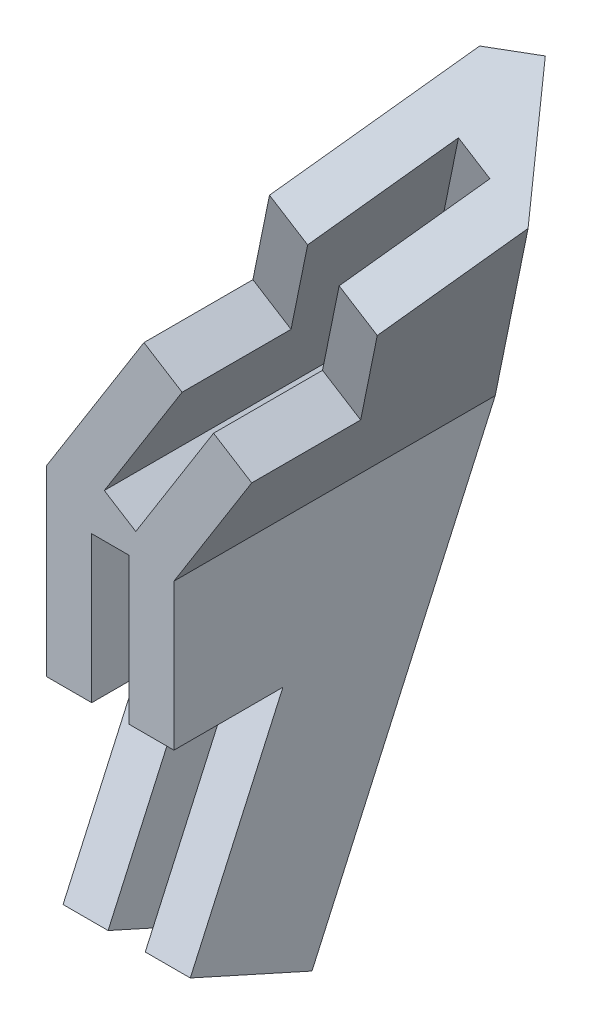
SolidWorks part; units mm, degrees
ref_plane "Front Plane" through (0, 0, 0) normal (0, 0, 1) x (1, 0, 0)
ref_plane "Top Plane" through (0, 0, 0) normal (0, 1, 0) x (1, 0, 0)
ref_plane "Right Plane" through (0, 0, 0) normal (1, 0, 0) x (0, 0, -1)
sketch "Sketch7" plane through (0, 0, 0) normal (0, 0, 1) x (1, 0, 0)
  line L0 (-1.7, -2) -> (-1.7, -15)
  line L1 (-1.7, -15) -> (-5.7, -15)
  line L2 (-5.7, -15) -> (-5.7, -2)
  line L3 (-5.7, -2) -> (-9, -2)
  line L4 (-9, -2) -> (-9, -15)
  line L5 (-9, -15) -> (-13, -15)
  line L7 (-13, -15) -> (-13, 1.2509)
  line L9 (-1.7, -2) -> (-13, 1.2509)
extrude "Boss-Extrude3" add sketch "Sketch7" along normal blind 30
sketch "Sketch11" plane through (-13, 0, 0) normal (-1, 0, 0) x (0, 0, 1)
  line L0 (0, 1.2509) -> (7.3231, -15)
  line L2 (30, -15) -> (0, -15) construction
  line L3 (7.3231, -15) -> (0, -15)
  line L4 (0, -15) -> (0, 1.2509)
extrude "Cut-Extrude1" cut sketch "Sketch11" against normal through all
sketch "Sketch12" plane through (0, -15, 0) normal (0, -1, 0) x (-1, 0, 0)
  line L0 (13, -7.3231) -> (9, -7.3231)
  line L1 (9, -7.3231) -> (9, -20.3231)
  line L2 (9, -30) -> (9, -7.3231) construction
  line L3 (13, -7.3231) -> (13, -20.3231)
  line L4 (13, -30) -> (13, -7.3231) construction
  line L5 (13, -20.3231) -> (9, -20.3231)
  line L6 (1.7, -7.3231) -> (1.7, -20.3231)
  line L7 (1.7, -30) -> (1.7, -7.3231) construction
  line L8 (1.7, -20.3231) -> (5.7, -20.3231)
  line L9 (5.7, -30) -> (5.7, -7.3231) construction
  line L10 (5.7, -20.3231) -> (5.7, -7.3231)
  line L11 (5.7, -7.3231) -> (1.7, -7.3231)
extrude "Boss-Extrude4" add sketch "Sketch12" along direction (0, 0.9117, -0.4108) on the side of the normal blind 30
sketch "Sketch18" plane through (0, -42.3512, 0) normal (0, -1, 0) x (-1, 0, 0)
  line L0 (1.7, -19.6483) -> (13, -19.6483)
  line L1 (13, -19.6483) -> (13, -8.3483)
  line L2 (1.7, -19.6483) -> (13, -8.3483)
  point P4 (0, 0)
  point P7 (0, 0)
  point P8 (0, 0)
  point P9 (13, -8.2679)
extrude "Boss-Extrude9" add sketch "Sketch18" along direction (0, 0.9117, -0.4108) on the side against the normal up to surface (44.259 mm away)
sketch "Sketch19" plane through (-13, 0, 0) normal (-1, 0, 0) x (0, 0, 1)
  line L0 (8.3483, -42.3512) -> (28.5467, -33.2493)
  line L1 (32.6483, -42.3512) -> (20.3231, -15) construction
  line L2 (28.5467, -33.2493) -> (32.6483, -42.3512)
  line L3 (32.6483, -42.3512) -> (8.3483, -42.3512)
extrude "Cut-Extrude3" cut sketch "Sketch19" against normal through all
sketch "Sketch20" plane through (0, -38.3298, 17.2724) normal (0, -0.9117, 0.4108) x (-1, 0, 0)
  line L0 (1.7, -0.5139) -> (10.0504, 7.0992) construction
  line L1 (13, 9.7884) -> (1.7, -0.5139) construction
  line L2 (10.0504, 7.0992) -> (13, 4.1492)
  line L3 (13, -12.3661) -> (13, 9.7884) construction
  line L4 (13, 4.1492) -> (13, 9.7884)
  line L5 (13, 9.7884) -> (10.0504, 7.0992)
  line L6 (13, 4.1492) -> (13, 9.7884)
  line M2 (13, -12.3661) -> (13, 9.7884)
  line M3 (13, 9.7884) -> (1.7, -0.5139)
extrude "Cut-Extrude4" cut sketch "Sketch20" against normal up to surface (45.2835 mm away) contours L2 M3 M2
mirror "Mirror3" about plane through (-1.7, -2, 30) normal (-0.2765, -0.961, 0) of bodies 132
